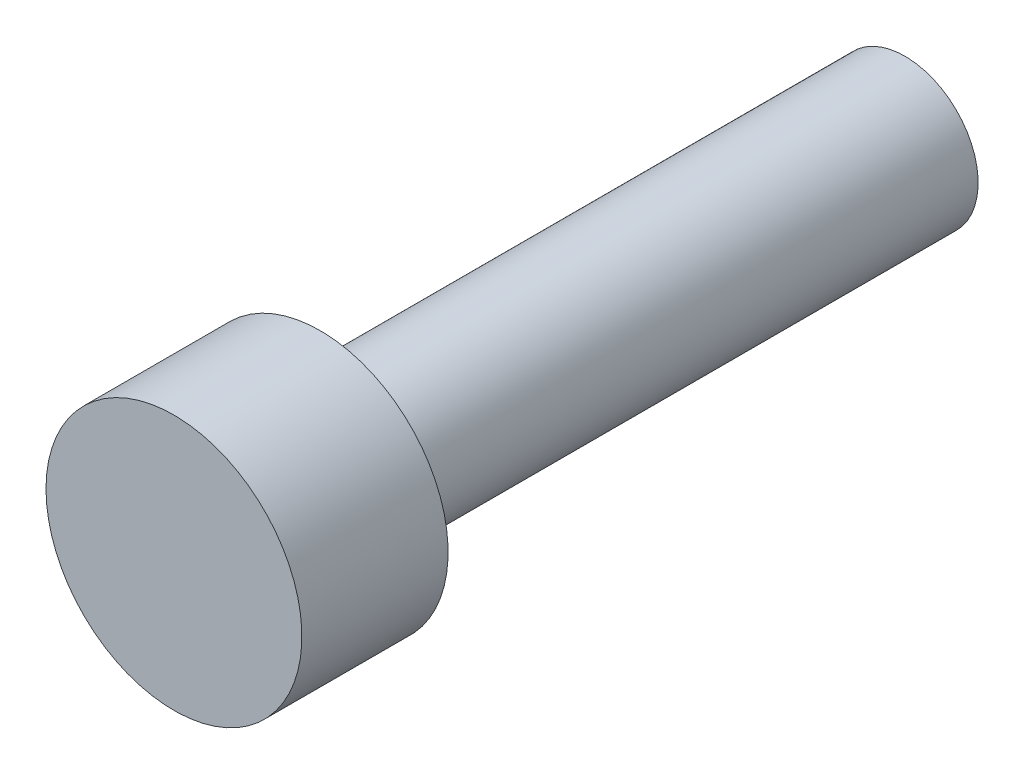
SolidWorks part; units mm, degrees
material "1.1191 (C45E)"
ref_plane "Front Plane" through (0, 0, 0) normal (0, 0, 1) x (1, 0, 0)
ref_plane "Top Plane" through (0, 0, 0) normal (0, 1, 0) x (1, 0, 0)
ref_plane "Right Plane" through (0, 0, 0) normal (1, 0, 0) x (0, 0, -1)
sketch "Sketch1" plane through (0, 0, 0) normal (0, 1, 0) x (1, 0, 0)
  line L0 (0, -4) -> (3.5, -4)
  line L1 (3.5, -4) -> (3.5, 0)
  line L2 (3.5, 0) -> (2, 0)
  line L3 (2, 0) -> (2, 16)
  line L4 (2, 16) -> (0, 16)
  line L5 (0, 16) -> (0, -4) construction
  line L6 (0, -4) -> (0, 16)
revolve "REV_ISO4762_M4x16_8.8" add sketch "Sketch1" angle 360 about L5
